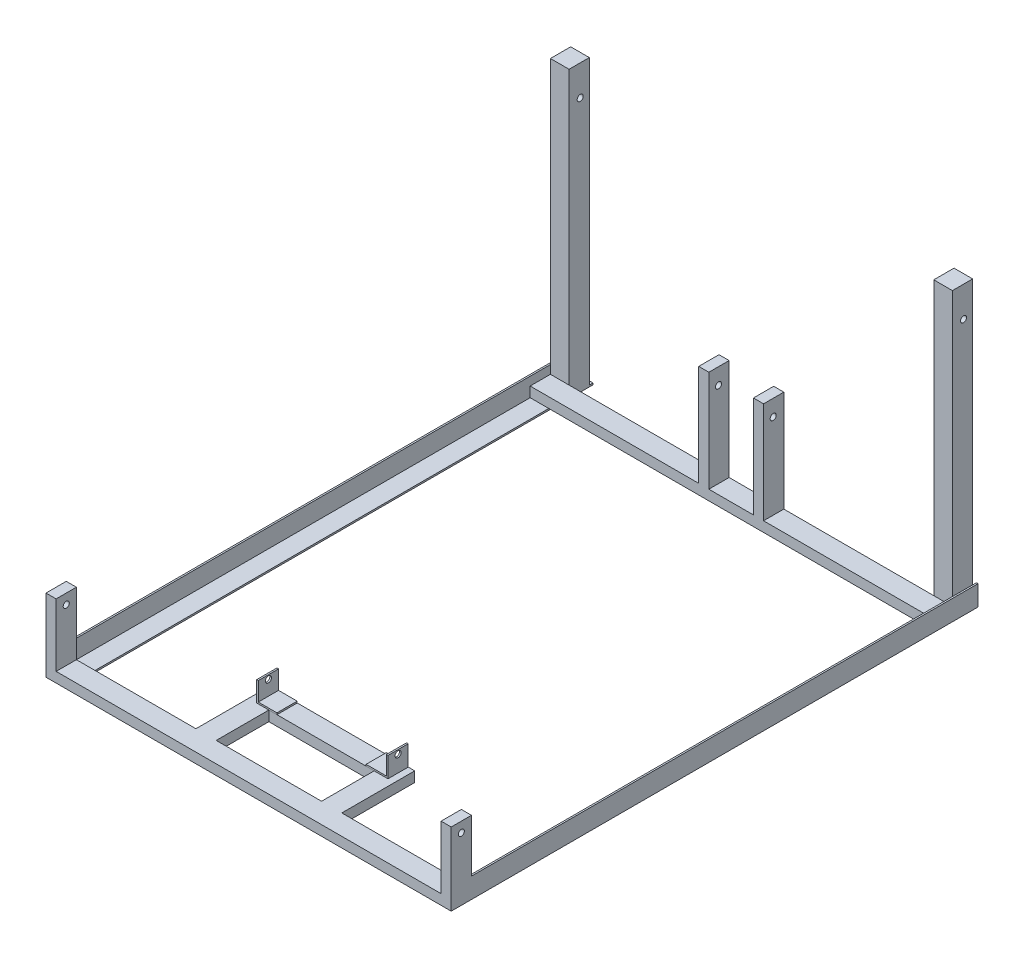
SolidWorks part; units mm, degrees
ref_plane "Front Plane" through (0, 0, 0) normal (0, 0, 1) x (1, 0, 0)
ref_plane "Top Plane" through (0, 0, 0) normal (0, 1, 0) x (1, 0, 0)
ref_plane "Right Plane" through (0, 0, 0) normal (1, 0, 0) x (0, 0, -1)
sketch "Sketch1" plane through (0, 0, 0) normal (0, 0, 1) x (1, 0, 0)
  line L0 (-915.8308, 0) -> (34.1692, 0)
  line L1 (34.1692, 0) -> (34.1692, 155)
  line L2 (34.1692, 155) -> (59.1692, 155)
  line L3 (59.1692, 155) -> (59.1692, -25)
  line L4 (59.1692, -25) -> (-940.8308, -25)
  line L5 (-940.8308, -25) -> (-940.8308, 155)
  line L6 (-940.8308, 155) -> (-915.8308, 155)
  line L7 (-915.8308, 155) -> (-915.8308, 0)
  dimension "D1" = 950
  dimension "D2" = 25
  dimension "D3" = 25
  dimension "D4" = 1000
extrude "Boss-Extrude1" add sketch "Sketch1" against normal blind 50
sketch "Sketch2" plane through (0, 0, 0) normal (0, 0, 1) x (1, 0, 0)
  line L0 (34.1692, 0) -> (-915.8308, 0) construction
  line L1 (-260.8308, 0) -> (-620.8308, 0)
  line L2 (-260.8308, 0) -> (-260.8308, -25)
  line L3 (-260.8308, -25) -> (-620.8308, -25)
  line L4 (-620.8308, 0) -> (-620.8308, -25)
  line L5 (-940.8308, -25) -> (59.1692, -25) construction
  line L6 (59.1692, -25) -> (59.1692, 155) construction
  dimension "D1" = 360
  dimension "D2" = 320
extrude "Boss-Extrude3" add sketch "Sketch2" against normal blind 230
sketch "Sketch3" plane through (0, 0, 0) normal (0, 1, 0) x (1, 0, 0)
  line L0 (-260.8308, 230) -> (-620.8308, 230) construction
  line L1 (-570.8308, 180) -> (-310.8308, 180)
  line L2 (-570.8308, 180) -> (-570.8308, 50)
  line L3 (-570.8308, 50) -> (-310.8308, 50)
  line L4 (-310.8308, 180) -> (-310.8308, 50)
  line L5 (-620.8308, 230) -> (-620.8308, 50) construction
  dimension "D1" = 260
  dimension "D2" = 130
  dimension "D3" = 50
  dimension "D4" = 50
extrude "Cut-Extrude1" cut sketch "Sketch3" against normal blind 230
sketch "Sketch4" plane through (0, 0, -50) normal (0, 0, -1) x (-1, 0, 0)
  line L0 (-59.1692, 25) -> (-59.1692, -25)
  line L1 (-59.1692, -25) -> (-59.1692, 155) construction
  line L2 (-59.1692, -25) -> (-9.1692, -25)
  line L3 (260.8308, -25) -> (-59.1692, -25) construction
  line L4 (-9.1692, -25) -> (-9.1692, -21)
  line L5 (-9.1692, -21) -> (-55.1692, -21)
  line L6 (-55.1692, -21) -> (-55.1692, 25)
  line L7 (-55.1692, 25) -> (-59.1692, 25)
  dimension "D1" = 50
  dimension "D2" = 4
  dimension "D3" = 4
  dimension "D4" = 46
extrude "Boss-Extrude4" add sketch "Sketch4" along normal blind 1250
sketch "Sketch6" plane through (0, 0, -50) normal (0, 0, -1) x (-1, 0, 0)
  line L0 (940.8308, 25) -> (940.8308, -25)
  line L1 (940.8308, 155) -> (940.8308, -25) construction
  line L2 (940.8308, -25) -> (890.8308, -25)
  line L3 (940.8308, -25) -> (620.8308, -25) construction
  line L4 (890.8308, -25) -> (890.8308, -21)
  line L5 (890.8308, -21) -> (936.8308, -21)
  line L6 (936.8308, -21) -> (936.8308, 25)
  line L7 (936.8308, 25) -> (940.8308, 25)
  dimension "D1" = 50
  dimension "D2" = 4
extrude "Boss-Extrude5" add sketch "Sketch6" along normal blind 1250
sketch "Sketch7" plane through (0, -21, 0) normal (0, 1, 0) x (1, 0, 0)
  line L0 (-890.8308, 1300) -> (-890.8308, 50) construction
  line L1 (-890.8308, 1290.8184) -> (-936.8308, 1290.8184)
  line L2 (-890.8308, 1290.8184) -> (-890.8308, 1240.8184)
  line L3 (-890.8308, 1240.8184) -> (-936.8308, 1240.8184)
  line L4 (-936.8308, 1290.8184) -> (-936.8308, 1240.8184)
  line L5 (-936.8308, 1300) -> (-936.8308, 50) construction
  line L6 (55.1692, 1240.8184) -> (9.1692, 1240.8184)
  line L7 (55.1692, 1290.8184) -> (9.1692, 1290.8184)
  line L8 (55.1692, 1290.8184) -> (55.1692, 1240.8184)
  line L9 (9.1692, 1290.8184) -> (9.1692, 1240.8184)
  dimension "D1" = 50
  dimension "D2" = 2
extrude "Boss-Extrude6" add sketch "Sketch7" along normal blind 700
sketch "Sketch10" plane through (-936.8308, 0, 0) normal (1, 0, 0) x (0, 0, -1)
  line L0 (1240.8184, -21) -> (50, -21) construction
  line L1 (1190.8184, -21) -> (1240.8184, -21)
  line L2 (1190.8184, -21) -> (1190.8184, 4)
  line L3 (1190.8184, 4) -> (1240.8184, 4)
  line L4 (1240.8184, -21) -> (1240.8184, 4)
  line L5 (1240.8184, 25) -> (1240.8184, -21) construction
  dimension "D1" = 25
  dimension "D2" = 50
extrude "Boss-Extrude7" add sketch "Sketch10" along normal blind 992
sketch "Sketch11" plane through (-940.8308, 0, 0) normal (-1, 0, 0) x (0, 0, 1)
  line L0 (-50, 155) -> (0, 155) construction
  line L2 (0, 155) -> (0, -25) construction
  circle A0 centre (-25, 130) radius 7.5
  dimension "D1" = 25
  dimension "D2" = 25
extrude "Cut-Extrude2" cut sketch "Sketch11" against normal blind 1012
sketch "Sketch12" plane through (0, 0, 0) normal (0, 1, 0) x (1, 0, 0)
  line L0 (-620.8308, 230) -> (-620.8308, 50) construction
  line L1 (-600.8308, 229.9116) -> (-550.8308, 229.9116)
  line L2 (-600.8308, 229.9116) -> (-600.8308, 179.9116)
  line L3 (-600.8308, 179.9116) -> (-550.8308, 179.9116)
  line L4 (-550.8308, 229.9116) -> (-550.8308, 179.9116)
  line L5 (-330.8308, 229.9116) -> (-330.8308, 179.9116)
  line L6 (-330.8308, 229.9116) -> (-280.8308, 229.9116)
  line L7 (-280.8308, 229.9116) -> (-280.8308, 179.9116)
  line L8 (-330.8308, 179.9116) -> (-280.8308, 179.9116)
  dimension "D1" = 50
  dimension "D2" = 50
  dimension "D3" = 20
  dimension "D4" = 2
extrude "Boss-Extrude8" add sketch "Sketch12" along normal blind 4
sketch "Sketch13" plane through (0, 0, 0) normal (0, 1, 0) x (1, 0, 0)
  line L0 (-600.8308, 179.9116) -> (-570.8308, 179.9116) construction
  line L1 (-600.8308, 229.9116) -> (-596.8308, 229.9116)
  line L2 (-600.8308, 229.9116) -> (-600.8308, 179.9116)
  line L3 (-600.8308, 179.9116) -> (-596.8308, 179.9116)
  line L4 (-596.8308, 229.9116) -> (-596.8308, 179.9116)
  line L5 (-280.8308, 229.9116) -> (-280.8308, 179.9116)
  line L6 (-276.8308, 229.9116) -> (-276.8308, 179.9116)
  line L7 (-280.8308, 179.9116) -> (-276.8308, 179.9116)
  line L8 (-280.8308, 229.9116) -> (-276.8308, 229.9116)
  dimension "D1" = 4
  dimension "D2" = 2
extrude "Boss-Extrude9" add sketch "Sketch13" along normal blind 50
sketch "Sketch15" plane through (-600.8308, 0, 0) normal (-1, 0, 0) x (0, 0, 1)
  line L0 (-229.9116, 50) -> (-179.9116, 50) construction
  line L2 (-179.9116, 50) -> (-179.9116, 0) construction
  circle A0 centre (-204.9116, 40) radius 7.5
  dimension "D1" = 15
  dimension "D2" = 10
  dimension "D3" = 25
extrude "Cut-Extrude3" cut sketch "Sketch15" against normal blind 380
sketch "Sketch16" plane through (0, 0, 0) normal (1, 0, 0) x (0, 0, -1)
  line L0 (1290.8184, 679) -> (1240.8184, 679) construction
  line L2 (1290.8184, 679) -> (1290.8184, 25) construction
  circle A0 centre (1268.3184, 604) radius 7.5
  dimension "D1" = 15
  dimension "D2" = 75
  dimension "D3" = 22.5
extrude "Cut-Extrude5" cut sketch "Sketch16" against normal through all and the other way through all
sketch "Sketch17" plane through (0, 4, 0) normal (0, 1, 0) x (1, 0, 0)
  line L0 (9.1692, 1240.8184) -> (-890.8308, 1240.8184) construction
  line L1 (-520.8308, 1240.8184) -> (-495.8308, 1240.8184)
  line L2 (-520.8308, 1240.8184) -> (-520.8308, 1190.8184)
  line L3 (-520.8308, 1190.8184) -> (-495.8308, 1190.8184)
  line L4 (-495.8308, 1240.8184) -> (-495.8308, 1190.8184)
  line L5 (55.1692, 1190.8184) -> (-936.8308, 1190.8184) construction
  line L6 (-940.8308, 1300) -> (-940.8308, 50) construction
  line L7 (-385.8308, 1240.8184) -> (-360.8308, 1240.8184)
  line L8 (-385.8308, 1240.8184) -> (-385.8308, 1190.8184)
  line L9 (-360.8308, 1240.8184) -> (-360.8308, 1190.8184)
  line L10 (-385.8308, 1190.8184) -> (-360.8308, 1190.8184)
  dimension "D1" = 25
  dimension "D2" = 420
  dimension "D3" = 2
extrude "Boss-Extrude10" add sketch "Sketch17" along normal blind 250
sketch "Sketch18" plane through (-520.8308, 0, 0) normal (-1, 0, 0) x (0, 0, 1)
  line L0 (-1240.8184, 254) -> (-1190.8184, 254) construction
  circle A0 centre (-1214.5922, 214) radius 7.5
  dimension "D1" = 15
  dimension "D2" = 40
extrude "Cut-Extrude6" cut sketch "Sketch18" against normal blind 250
